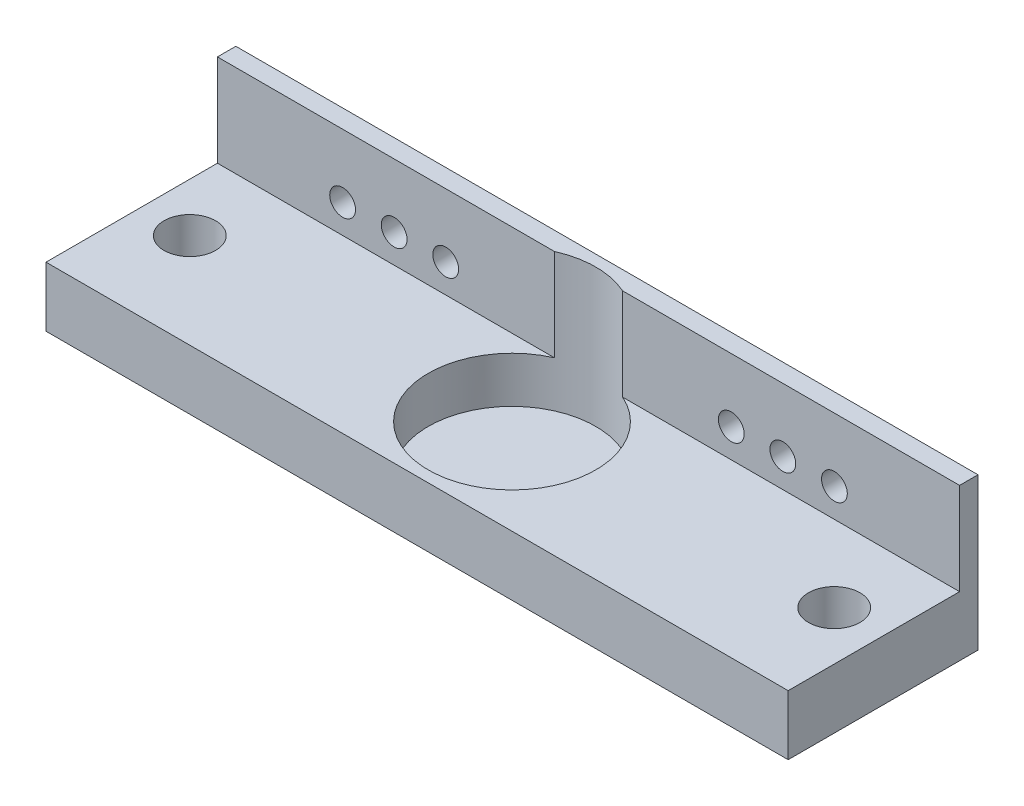
SolidWorks part; units mm, degrees
ref_plane "Front Plane" through (0, 0, 0) normal (0, 0, 1) x (1, 0, 0)
ref_plane "Top Plane" through (0, 0, 0) normal (0, 1, 0) x (1, 0, 0)
ref_plane "Right Plane" through (0, 0, 0) normal (1, 0, 0) x (0, 0, -1)
sketch "Sketch1" plane through (0, 0, 0) normal (0, 1, 0) x (1, 0, 0)
  line L1 (51.195, -13.095) -> (-51.195, -13.095)
  line L2 (51.195, -13.095) -> (51.195, 13.095)
  line L3 (51.195, 13.095) -> (-51.195, 13.095)
  line L4 (-51.195, -13.095) -> (-51.195, 13.095)
  line L5 (51.195, -13.095) -> (-51.195, 13.095) construction
  line L6 (51.195, 13.095) -> (-51.195, -13.095) construction
  point P0 (0, 0)
  dimension "D1" = 102.39
  dimension "D2" = 26.19
extrude "Boss-Extrude1" add sketch "Sketch1" along normal blind 1.905
sketch "Sketch2" plane through (0, 1.905, 0) normal (0, 1, 0) x (1, 0, 0)
  line L6 (51.195, -13.095) -> (-51.195, -13.095)
  line L7 (51.195, -13.095) -> (51.195, 13.095)
  line L8 (51.195, 13.095) -> (-51.195, 13.095)
  line L9 (-51.195, 13.095) -> (-51.195, -13.095)
  line L10 (-51.195, -13.095) -> (51.195, -13.095)
  line L11 (51.195, -13.095) -> (51.195, 13.095)
  line L12 (51.195, 13.095) -> (-51.195, 13.095)
  line L13 (-51.195, 13.095) -> (-51.195, -13.095)
  line L14 (-51.195, -13.095) -> (51.195, -13.095)
  line L15 (51.195, -13.095) -> (51.195, 13.095)
  line L16 (51.195, 13.095) -> (-51.195, 13.095)
  line L17 (-51.195, -13.095) -> (-51.195, 13.095)
  line L18 (51.195, -13.095) -> (-51.195, 13.095) construction
  line L19 (51.195, 13.095) -> (-51.195, -13.095) construction
  circle A0 centre (0, 0) radius 11.557
  circle A1 centre (-44.45, 0) radius 3.556
  circle A2 centre (44.45, 0) radius 3.556
  dimension "D1" = 23.114
  dimension "D2" = 7.112
  dimension "D3" = 7.112
  dimension "D4" = 44.45
  dimension "D5" = 44.45
  dimension "D19" = 0
extrude "Boss-Extrude3" add sketch "Sketch2" along normal blind 6.35
sketch "Sketch3" plane through (0, 8.255, 0) normal (0, 1, 0) x (1, 0, 0)
  line L0 (51.195, -13.095) -> (51.195, 13.095) construction
  line L1 (-51.195, 13.095) -> (51.195, 13.095)
  line L2 (-51.195, 13.095) -> (-51.195, 10.555)
  line L4 (51.195, 13.095) -> (51.195, 10.555)
  line L6 (-51.195, 10.555) -> (-4.707, 10.555)
  line L7 (4.707, 10.555) -> (51.195, 10.555)
  circle A2 centre (0, 0) radius 11.557 construction
  circle A3 centre (0, 0) radius 11.557 construction
  arc A4 (-4.707, 10.555) -> (4.707, 10.555) centre (0, 0) cw
  point P7 (-4.1421, 13.7392)
  point P14 (0, 0)
  point P15 (0, 0)
  dimension "D1" = 2.54
extrude "Boss-Extrude4" add sketch "Sketch3" along normal blind 12.7 contours L6 A4 L7 L4 L1 L2
sketch "Sketch4" plane through (0, 0, -13.095) normal (0, 0, -1) x (-1, 0, 0)
  line L2 (57.455, 14.211) -> (-57.545, 14.211) construction
  line L3 (57.455, 10.211) -> (-57.545, 10.211) construction
  line L4 (-51.195, 0) -> (51.195, 0)
  line L5 (51.195, 0) -> (51.195, 20.955)
  line L6 (51.195, 20.955) -> (-51.195, 20.955)
  line L7 (-51.195, 20.955) -> (-51.195, 0)
  line L8 (-51.195, 0) -> (51.195, 0)
  line L9 (51.195, 0) -> (51.195, 20.955)
  line L10 (51.195, 20.955) -> (-51.195, 20.955)
  line L11 (-51.195, 20.955) -> (-51.195, 0)
  line L12 (-57.545, 14.211) -> (-57.545, 10.211) construction
  line L13 (-57.545, 10.211) -> (-57.7964, 10.4194)
  line L14 (-57.545, 12.211) -> (57.455, 12.211) construction
  circle A0 centre (-33.923, 12.211) radius 1.778
  circle A1 centre (-26.811, 12.211) radius 1.778
  circle A2 centre (-19.699, 12.211) radius 1.778
  circle A3 centre (19.699, 12.211) radius 1.778
  circle A4 centre (26.811, 12.211) radius 1.778
  circle A5 centre (33.923, 12.211) radius 1.778
  point P23 (0, 0)
  point P24 (0, 0)
  point P25 (2.0564, 35.2498)
  point P26 (0, 0)
  point P27 (-43.3155, 12.211)
  dimension "D7" = 3.556
  dimension "D2" = 7.112
  dimension "D3" = 7.112
  dimension "D4" = 39.398
  dimension "D5" = 7.112
  dimension "D6" = 7.112
  dimension "D8" = 17.272
  dimension "D1" = 0
extrude "Cut-Extrude1" cut sketch "Sketch4" against normal up to next contours A5 | A4 | A3 | A0 | A1 | A2
